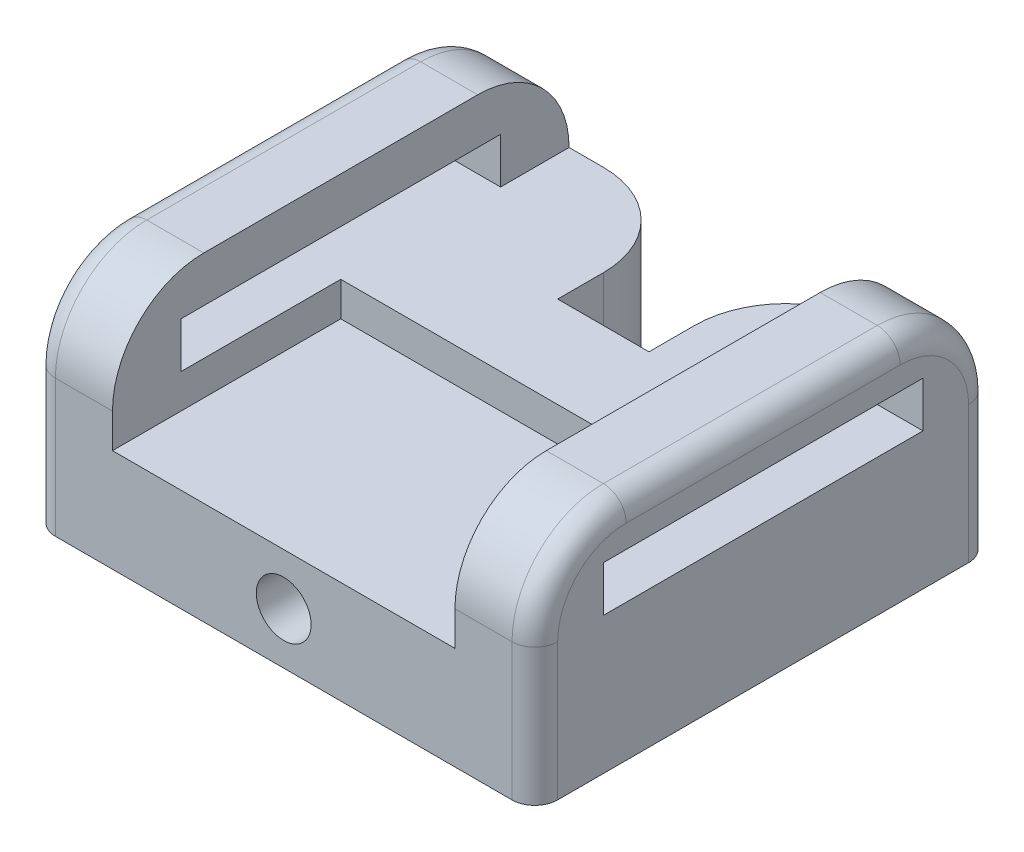
SolidWorks part; units mm, degrees
ref_plane "Front Plane" through (0, 0, 0) normal (0, 0, 1) x (1, 0, 0)
ref_plane "Top Plane" through (0, 0, 0) normal (0, 1, 0) x (1, 0, 0)
ref_plane "Right Plane" through (0, 0, 0) normal (1, 0, 0) x (0, 0, -1)
sketch "Sketch1" plane through (0, 0, 0) normal (0, 1, 0) x (1, 0, 0)
  line L1 (-115.333, -26.0606) -> (-104.333, -26.0606)
  line L2 (-115.333, -26.0606) -> (-115.333, -36.0606)
  line L3 (-115.333, -36.0606) -> (-104.333, -36.0606)
  line L4 (-104.333, -26.0606) -> (-104.333, -36.0606)
extrude "Boss-Extrude1" add sketch "Sketch1" along normal blind 3 contours L2 L1 L4 L3
sketch "Sketch2" plane through (0, 3, 0) normal (0, 1, 0) x (1, 0, 0)
  line L0 (-104.333, -36.0606) -> (-104.333, -35.0606)
  line L1 (-104.333, -26.0606) -> (-104.333, -36.0606) construction
  line L2 (-105.333, -27.0606) -> (-106.083, -27.0606)
  line L3 (-104.333, -26.0606) -> (-104.333, -27.0606)
  line L4 (-106.083, -35.0606) -> (-105.333, -35.0606)
  line L5 (-105.333, -27.0606) -> (-105.333, -35.0606)
  line L7 (-106.083, -27.0606) -> (-106.083, -35.0606)
  line L9 (-115.333, -26.0606) -> (-114.333, -26.0606)
  line L10 (-115.333, -26.0606) -> (-104.333, -26.0606) construction
  line L11 (-114.333, -26.0606) -> (-114.333, -27.0606)
  line L12 (-114.333, -27.0606) -> (-113.583, -27.0606)
  line L13 (-114.333, -27.0606) -> (-114.333, -35.0606)
  line L14 (-114.333, -35.0606) -> (-113.583, -35.0606)
  line L15 (-113.583, -35.0606) -> (-113.583, -27.0606)
  line L16 (-109.833, -36.0606) -> (-109.833, -29.0606)
  line L17 (-115.333, -36.0606) -> (-104.333, -36.0606) construction
  line L18 (-109.833, -29.0606) -> (-110.833, -29.0606)
  line L19 (-109.833, -29.0606) -> (-108.833, -29.0606)
  line L20 (-110.833, -29.0606) -> (-110.833, -26.0606)
  line L21 (-108.833, -29.0606) -> (-108.833, -26.0606)
  line L22 (-108.833, -26.0606) -> (-110.833, -26.0606)
  line M17 (-104.333, -26.0606) -> (-115.333, -26.0606)
extrude "Cut-Extrude4" cut sketch "Sketch2" against normal blind 12 contours L19 L21 L20 L18 M17
sketch "Sketch5" plane through (0, 3, 0) normal (0, 1, 0) x (1, 0, 0)
  line L0 (-109.833, -36.0606) -> (-113.583, -36.0606)
  line L1 (-115.333, -36.0606) -> (-104.333, -36.0606) construction
  line L2 (-109.833, -36.0606) -> (-106.083, -36.0606)
  line L3 (-113.583, -36.0606) -> (-113.583, -31.0606)
  line L4 (-113.583, -31.0606) -> (-106.083, -31.0606)
  line L5 (-106.083, -31.0606) -> (-106.083, -36.0606)
extrude "Cut-Extrude5" cut sketch "Sketch5" against normal blind 0.75
sketch "Sketch6" plane through (0, 3, 0) normal (0, 1, 0) x (1, 0, 0)
  line L0 (-113.583, -36.0606) -> (-113.583, -34.5606)
  line L1 (-113.583, -31.0606) -> (-113.583, -36.0606) construction
  line L2 (-113.583, -34.5606) -> (-115.333, -34.5606)
  line L3 (-115.333, -26.0606) -> (-115.333, -36.0606) construction
  line L4 (-115.333, -34.5606) -> (-115.333, -36.0606)
  line L5 (-115.333, -36.0606) -> (-113.583, -36.0606)
  line L6 (-115.333, -26.0606) -> (-115.333, -27.5606)
  line L7 (-115.333, -27.5606) -> (-113.583, -27.5606)
  line L8 (-113.583, -27.5606) -> (-113.583, -26.0606)
  line L9 (-115.333, -26.0606) -> (-110.833, -26.0606) construction
  line L10 (-113.583, -26.0606) -> (-115.333, -26.0606)
  line L11 (-104.333, -26.0606) -> (-104.333, -27.5606)
  line L12 (-104.333, -26.0606) -> (-104.333, -36.0606) construction
  line L13 (-104.333, -27.5606) -> (-106.083, -27.5606)
  line L14 (-106.083, -27.5606) -> (-106.083, -26.0606)
  line L15 (-108.833, -26.0606) -> (-104.333, -26.0606) construction
  line L16 (-106.083, -26.0606) -> (-104.333, -26.0606)
  line L17 (-106.083, -36.0606) -> (-106.083, -34.5606)
  line L18 (-106.083, -36.0606) -> (-106.083, -31.0606) construction
  line L19 (-106.083, -34.5606) -> (-104.333, -34.5606)
  line L20 (-104.333, -34.5606) -> (-104.333, -36.0606)
  line L21 (-104.333, -36.0606) -> (-106.083, -36.0606)
extrude "Boss-Extrude2" add sketch "Sketch6" along normal blind 1
sketch "Sketch7" plane through (0, 4, 0) normal (0, 1, 0) x (1, 0, 0)
  line L0 (-115.333, -26.0606) -> (-115.333, -36.0606)
  line L1 (-115.333, -36.0606) -> (-113.583, -36.0606)
  line L2 (-113.583, -36.0606) -> (-113.583, -26.0606)
  line L3 (-113.583, -26.0606) -> (-115.333, -26.0606)
  line L4 (-104.333, -36.0606) -> (-104.333, -26.0606)
  line L5 (-104.333, -26.0606) -> (-106.083, -26.0606)
  line L6 (-106.083, -26.0606) -> (-106.083, -36.0606)
  line L7 (-106.083, -36.0606) -> (-104.333, -36.0606)
extrude "Boss-Extrude3" add sketch "Sketch7" along normal blind 1
sketch "Sketch8" plane through (0, 0, 36.0606) normal (0, 0, 1) x (1, 0, 0)
  line L0 (-109.833, 2.25) -> (-109.833, 0)
  line L1 (-113.583, 2.25) -> (-106.083, 2.25) construction
  line L2 (-115.333, 0) -> (-104.333, 0) construction
  circle A0 centre (-109.833, 1.125) radius 0.6
extrude "Cut-Extrude6" cut sketch "Sketch8" against normal blind 12 contours L0 A0 | L0 A0
fillet "Fillet4" radius 2 2 edges at (-110.833, 1.5, 26.0606) (-108.833, 1.5, 26.0606)
fillet "Fillet5" radius 2 4 edges at (-105.208, 5, 26.0606) (-114.458, 5, 26.0606) (-105.208, 5, 36.0606) (-114.458, 5, 36.0606)
fillet "Fillet6" radius 0.5 5 edges at (-104.333, 4.4142, 26.6464) (-104.333, 5, 31.0606) (-104.333, 4.4142, 35.4748) (-104.333, 1.5, 36.0606) (-104.333, 1.5, 26.0606)
fillet "Fillet7" radius 0.5 5 edges at (-115.333, 1.5, 26.0606) (-115.333, 4.4142, 26.6464) (-115.333, 5, 31.0606) (-115.333, 4.4142, 35.4748) (-115.333, 1.5, 36.0606)
